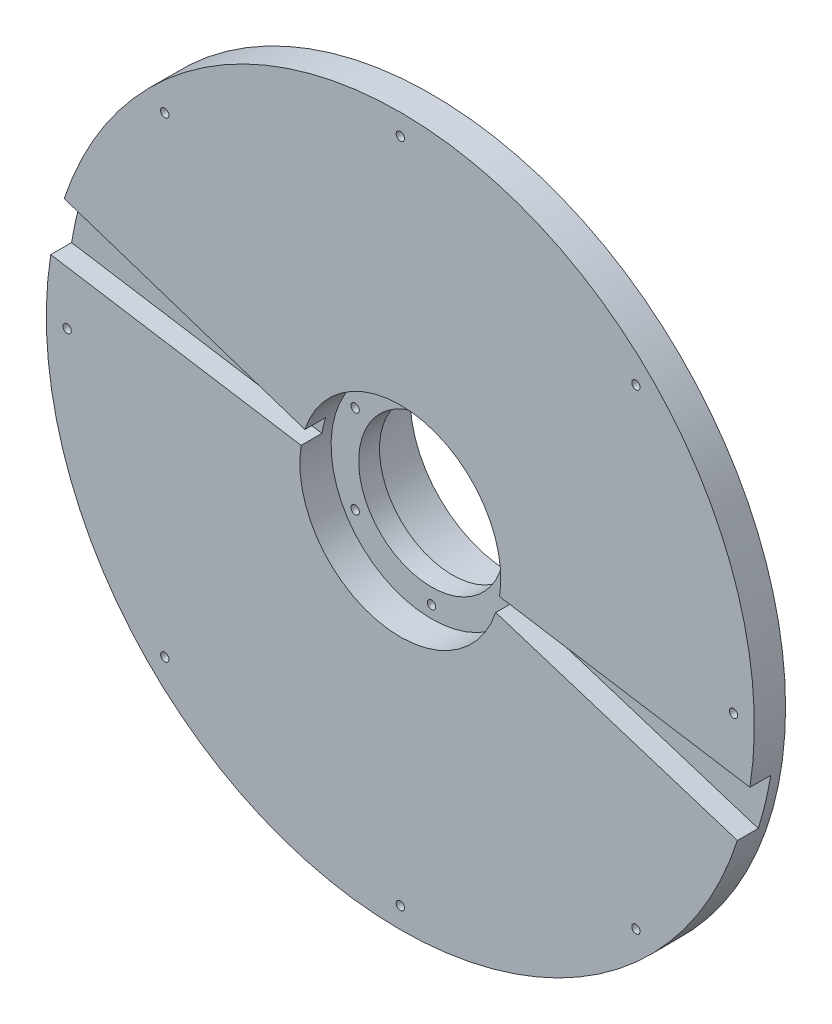
SolidWorks part; units mm, degrees
ref_plane "前视基准面" through (0, 0, 0) normal (0, 0, 1) x (1, 0, 0)
ref_plane "上视基准面" through (0, 0, 0) normal (0, 1, 0) x (1, 0, 0)
ref_plane "右视基准面" through (0, 0, 0) normal (1, 0, 0) x (0, 0, -1)
other "Configuration Table"
sketch "草图1" plane through (0, 0, 0) normal (0, 0, 1) x (1, 0, 0)
  circle A0 centre (0, 0) radius 60
extrude "凸台-拉伸1" add sketch "草图1" along normal blind 28
sketch "草图2" plane through (0, 0, 28) normal (0, 0, 1) x (1, 0, 0)
  circle A0 centre (0, 0) radius 48.25
extrude "切除-拉伸1" cut sketch "草图2" against normal through all
sketch "草图3" plane through (0, 0, 28) normal (0, 0, 1) x (1, 0, 0)
  circle A1 centre (0, 0) radius 48.25
sketch "草图4" plane through (0, 0, 28) normal (0, 0, 1) x (1, 0, 0)
  circle A0 centre (0, 0) radius 150
extrude "凸台-拉伸3" add sketch "草图4" along normal blind 10
sketch "草图5" plane through (0, 0, 38) normal (0, 0, 1) x (1, 0, 0)
  circle A0 centre (0, 0) radius 35
extrude "切除-拉伸2" cut sketch "草图5" against normal through all
sketch "草图6" plane through (0, 0, 38) normal (0, 0, 1) x (1, 0, 0)
  line L0 (0, -20.9) -> (0, 20.9) construction
  circle A1 centre (0, 42.3567) radius 2
extrude "切除-拉伸3" cut sketch "草图6" against normal through all
pattern_circular "阵列(圆周)1" count 6 over 360 about axis through (0, 0, 0) along (0, 0, 1) of "切除-拉伸3"
sketch "草图7" plane through (0, 0, 38) normal (0, 0, 1) x (1, 0, 0)
  circle A0 centre (0, 0) radius 48.25
  circle A2 centre (0, 0) radius 170
extrude "凸台-拉伸4" add sketch "草图7" along normal blind 15
sketch "草图9" plane through (0, 0, 38) normal (0, 0, -1) x (-1, 0, 0)
  circle A1 centre (0, 160) radius 2
extrude "切除-拉伸4" cut sketch "草图9" against normal through all
pattern_circular "阵列(圆周)2" count 8 over 360 about axis through (0, 0, 0) along (0, 0, 1) of "切除-拉伸4"
sketch "草图11" plane through (0, 0, 53) normal (0, 0, 1) x (1, 0, 0)
  line L1 (47.6453, -7.6148) -> (167.8695, -26.8295)
  line L2 (45.8107, -15.1473) -> (161.8688, -51.947)
  line L5 (-45.8107, 15.1473) -> (-161.4056, 53.3689)
  line L6 (-47.6453, 7.6148) -> (-167.8695, 26.8295)
  circle A0 centre (0, 0) radius 48.25 construction
  circle A1 centre (0, 0) radius 170 construction
  arc A4 (47.6453, -7.6148) -> (45.8107, -15.1473) centre (0, 0) cw
  arc A5 (167.8695, -26.8295) -> (161.8688, -51.947) centre (0, 0) cw
  arc A6 (-161.4056, 53.3689) -> (-167.8695, 26.8295) centre (0, 0) ccw
  arc A7 (-45.8107, 15.1473) -> (-47.6453, 7.6148) centre (0, 0) ccw
extrude "切除-拉伸5" cut sketch "草图11" against normal blind 10
